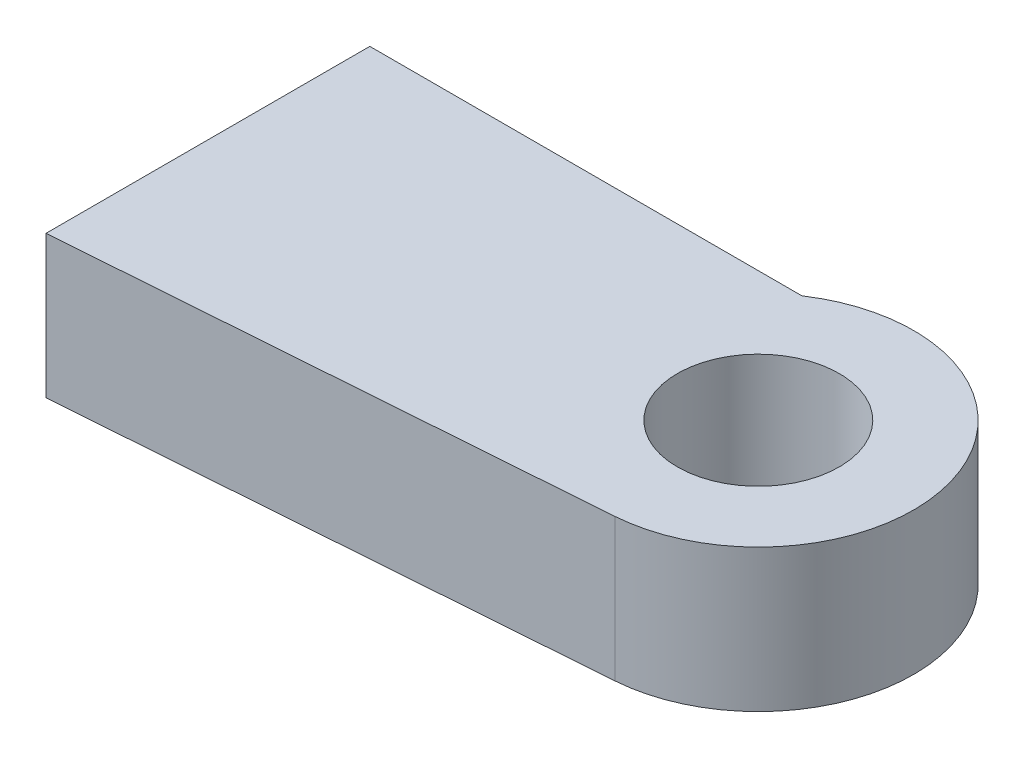
SolidWorks part; units mm, degrees
ref_plane "Front Plane" through (0, 0, 0) normal (0, 0, 1) x (1, 0, 0)
ref_plane "Top Plane" through (0, 0, 0) normal (0, 1, 0) x (1, 0, 0)
ref_plane "Right Plane" through (0, 0, 0) normal (1, 0, 0) x (0, 0, -1)
sketch "Sketch2" plane through (0, 0, 0) normal (0, 1, 0) x (1, 0, 0)
  line L0 (0, 0) -> (0, 20)
  line L1 (0, 20) -> (26.69, 20)
  line L2 (0, 0) -> (32.7068, 2.4263)
  circle A0 centre (31.9966, 12) radius 5
  arc A1 (32.7068, 2.4263) -> (26.69, 20) centre (31.9966, 12) ccw
  dimension "D1" = 9.6
  dimension "D2" = 10
  dimension "D3" = 8
  dimension "D4" = 20
  dimension "D5" = 31.9966
extrude "Boss-Extrude1" add sketch "Sketch2" along normal blind 8.8
